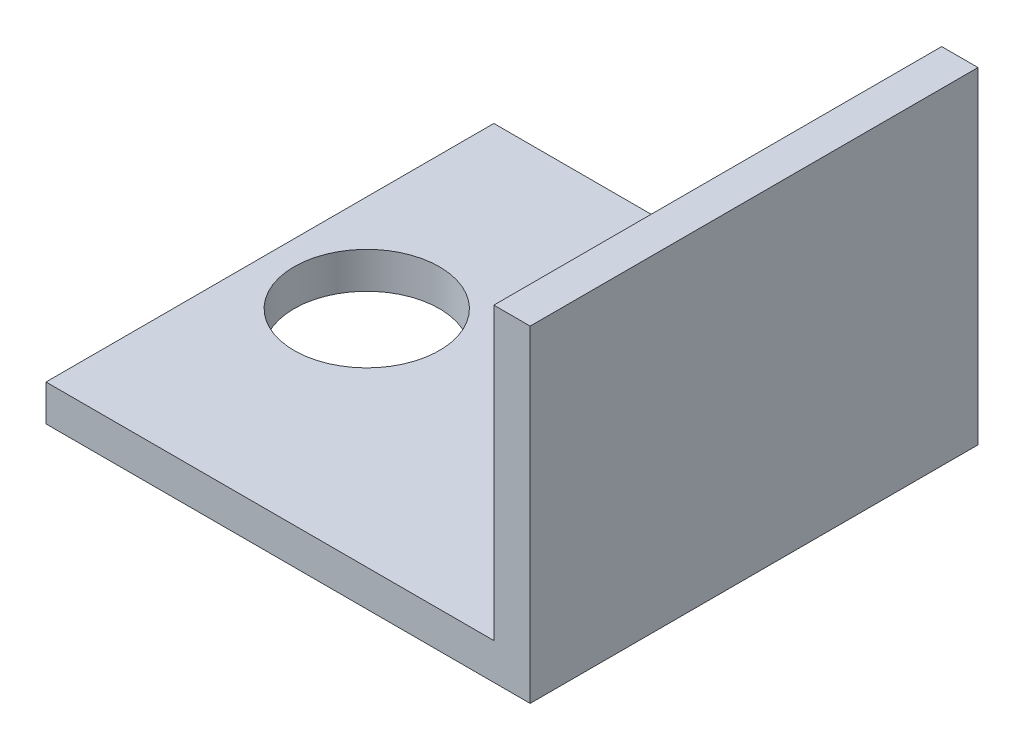
SolidWorks part; units mm, degrees
ref_plane "Front Plane" through (0, 0, 0) normal (0, 0, 1) x (1, 0, 0)
ref_plane "Top Plane" through (0, 0, 0) normal (0, 1, 0) x (1, 0, 0)
ref_plane "Right Plane" through (0, 0, 0) normal (1, 0, 0) x (0, 0, -1)
sketch "Sketch1" plane through (0, 0, 0) normal (0, 0, 1) x (1, 0, 0)
  line L0 (0, 0) -> (0, -27)
  line L1 (0, -27) -> (-40, -27)
  line L2 (-40, -27) -> (-40, -24)
  line L3 (-40, -24) -> (-3, -24)
  line L4 (-3, -24) -> (-3, 0)
  line L5 (-3, 0) -> (0, 0)
  dimension "D1" = 3
  dimension "D2" = 3
  dimension "D3" = 27
  dimension "D4" = 40
extrude "Boss-Extrude1" add sketch "Sketch1" along normal blind 37
sketch "Sketch2" plane through (0, -24, 0) normal (0, 1, 0) x (1, 0, 0)
  line L0 (-3, 0) -> (-40, 0) construction
  line L1 (-40, -37) -> (-40, 0) construction
  circle A0 centre (-32, -18.5) radius 6
  dimension "D1" = 18.5
  dimension "D2" = 12
  dimension "D3" = 8
extrude "Cut-Extrude1" cut sketch "Sketch2" against normal blind 35
